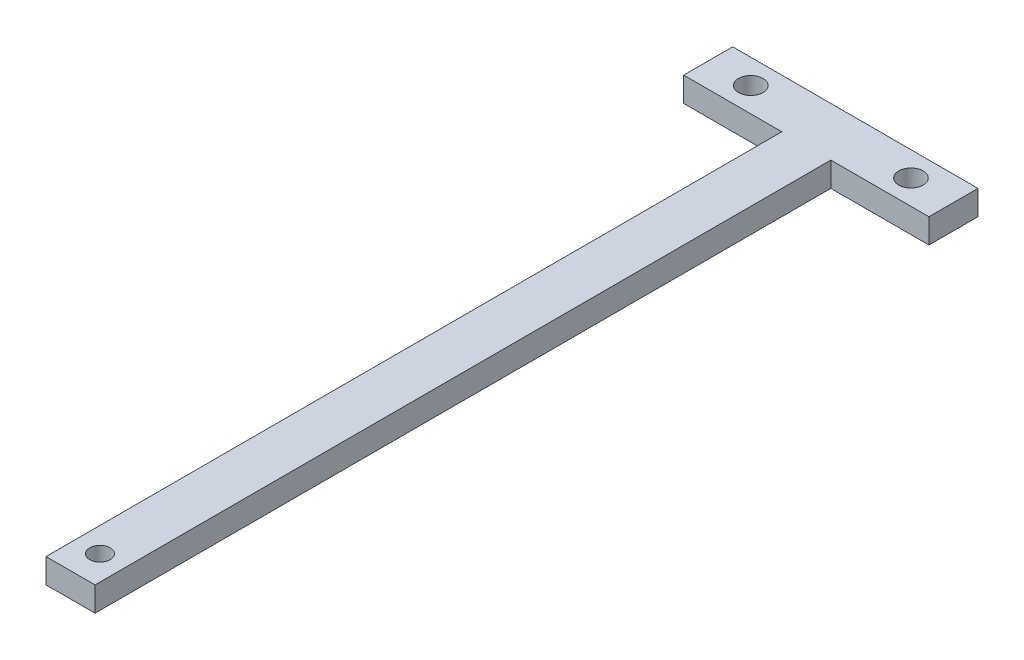
SolidWorks part; units mm, degrees
ref_plane "Front Plane" through (0, 0, 0) normal (0, 0, 1) x (1, 0, 0)
ref_plane "Top Plane" through (0, 0, 0) normal (0, 1, 0) x (1, 0, 0)
ref_plane "Right Plane" through (0, 0, 0) normal (1, 0, 0) x (0, 0, -1)
sketch "Sketch1" plane through (0, 0, 0) normal (0, 1, 0) x (1, 0, 0)
  line L0 (0, 0) -> (0, 150)
  line L1 (0, 150) -> (-20, 150)
  line L2 (10, 0) -> (10, 150)
  line L3 (10, 160) -> (-20, 160)
  line L4 (10, 160) -> (30, 160)
  line L5 (20, 150) -> (30, 150)
  line L6 (20, 150) -> (10, 150)
  line L7 (-20, 150) -> (-20, 160)
  line L8 (0, 150) -> (5, 150) construction
  line L9 (5, 150) -> (5, 126.9076) construction
  line L10 (30, 150) -> (30, 160)
  line L11 (10, 0) -> (10, 160) construction
  line L12 (0, 0) -> (10, 0)
  line L13 (10, 0) -> (10.5494, 0.0329)
  line L14 (-20, 155) -> (30, 155) construction
  line L15 (5, 0) -> (5, 14.4954) construction
  circle A0 centre (-11.3269, 155) radius 2.5
  circle A1 centre (21.3269, 155) radius 2.5
  circle A2 centre (5, 6) radius 2.0953
  dimension "D4" = 5
  dimension "D6" = 6
  dimension "D1" = 150
  dimension "D2" = 20
  dimension "D5" = 0
  dimension "D3" = 10
extrude "Boss-Extrude1" add sketch "Sketch1" along normal blind 5 contours L0 L12 L2 L6 L5 L10 L4 L3 L7 L1 A0 A1
